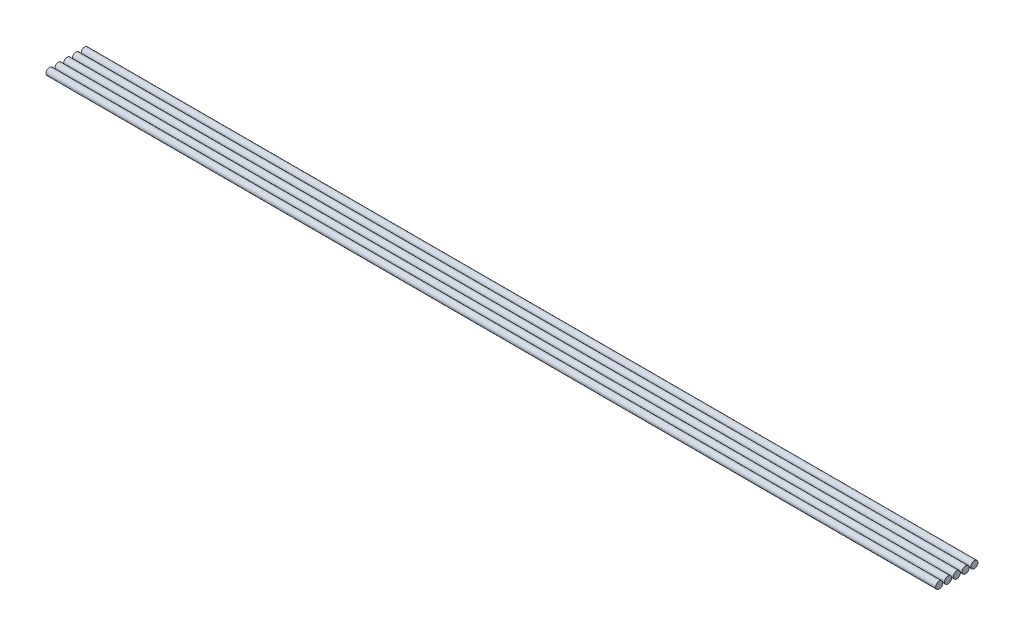
SolidWorks part; units mm, degrees
ref_plane "Front Plane" through (0, 0, 0) normal (0, 0, 1) x (1, 0, 0)
ref_plane "Top Plane" through (0, 0, 0) normal (0, 1, 0) x (1, 0, 0)
ref_plane "Right Plane" through (0, 0, 0) normal (1, 0, 0) x (0, 0, -1)
sketch "Sketch3" plane through (0, 0, 0) normal (0, 1, 0) x (1, 0, 0)
  line L0 (0, 2) -> (101, 2)
  line L1 (0, 1) -> (101, 1)
  line L2 (0, 0) -> (101, 0)
  line L3 (0, -1) -> (101, -1)
  line L4 (0, -2) -> (101, -2)
  line L5 (0, 2) -> (0, -2) construction
  line L6 (101, 2) -> (101, -2) construction
  point P10 (50, 1)
  point P11 (0, 0)
  dimension "D1" = 1
  dimension "D2" = 1
  dimension "D3" = 1
  dimension "D4" = 1
  dimension "D5" = 101
sketch "Sketch21" plane through (0, 0, 0) normal (1, 0, 0) x (0, 0, -1)
  line L0 (2, 0) -> (-2, 0) construction
  circle A0 centre (2, 0) radius 0.4
  circle A1 centre (1, 0) radius 0.4
  circle A2 centre (0, 0) radius 0.4
  circle A3 centre (-1, 0) radius 0.4
  circle A4 centre (-2, 0) radius 0.4
  dimension "D1" = 0.8
sweep "Sweep2" add profiles "Sketch21" path "Sketch3"
